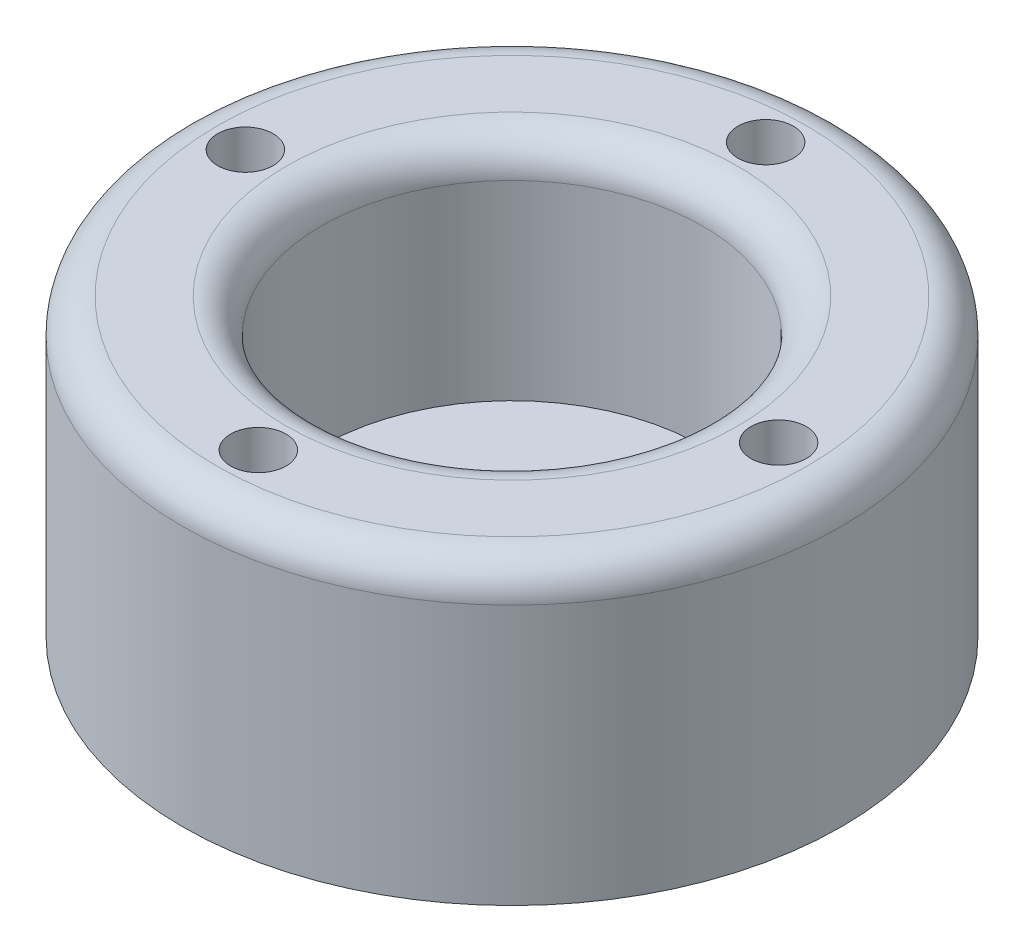
SolidWorks part; units mm, degrees
ref_plane "Ön Düzlem" through (0, 0, 0) normal (0, 0, 1) x (1, 0, 0)
ref_plane "Üst Düzlem" through (0, 0, 0) normal (0, 1, 0) x (1, 0, 0)
ref_plane "Sağ Düzlem" through (0, 0, 0) normal (1, 0, 0) x (0, 0, -1)
sketch "Sketch1" plane through (0, 0, 0) normal (0, 1, 0) x (1, 0, 0)
  circle A0 centre (0, 0) radius 4.75
  circle A1 centre (0, 0) radius 19
  dimension "D1" = 9.5
  dimension "D2" = 38
extrude "Boss-Extrude1" add sketch "Sketch1" along normal blind 17
sketch "Sketch2" plane through (0, 17, 0) normal (0, 1, 0) x (1, 0, 0)
  circle A0 centre (-0.3738, 7.25) radius 1.25
  circle A1 centre (7.25, 0.3738) radius 1.25
  circle A2 centre (0.3738, -7.25) radius 1.25
  circle A3 centre (-7.25, -0.3738) radius 1.25
  dimension "D1" = 7.25
  dimension "D2" = 2.5
  dimension "D3" = 4
extrude "Cut-Extrude1" cut sketch "Sketch2" against normal through all
sketch "Sketch3" plane through (0, 17, 0) normal (0, 1, 0) x (1, 0, 0)
  line L0 (-0.3738, 7.25) -> (-0.3738, 18.2914) construction
  circle A0 centre (-0.3738, 15) radius 1.6
  circle A1 centre (15, 0.3738) radius 1.6
  circle A2 centre (0.3738, -15) radius 1.6
  circle A3 centre (-15, -0.3738) radius 1.6
  dimension "D1" = 4
  dimension "D2" = 15
extrude "Cut-Extrude2" cut sketch "Sketch3" against normal blind 15
sketch "Sketch4" plane through (0, 17, 0) normal (0, 1, 0) x (1, 0, 0)
  circle A0 centre (0, 0) radius 4.75 construction
  circle A1 centre (0, 0) radius 19
  circle A2 centre (0, 0) radius 19
  circle A3 centre (0, 0) radius 4.75
  circle A4 centre (0, 0) radius 11
  circle M6 centre (-0.3738, 7.25) radius 1.25
  circle M7 centre (7.25, 0.3738) radius 1.25
  circle M8 centre (0.3738, -7.25) radius 1.25
  circle M9 centre (-7.25, -0.3738) radius 1.25
  circle M11 centre (0, 0) radius 4.75
  dimension "D2" = 22
  dimension "D1" = 0
extrude "Cut-Extrude4" cut sketch "Sketch4" against normal blind 13 contours A4 M6 M8 M11 M9 M7
fillet "Fillet3" radius 2 2 edges at (0, 17, 19) (0, 17, 11)
